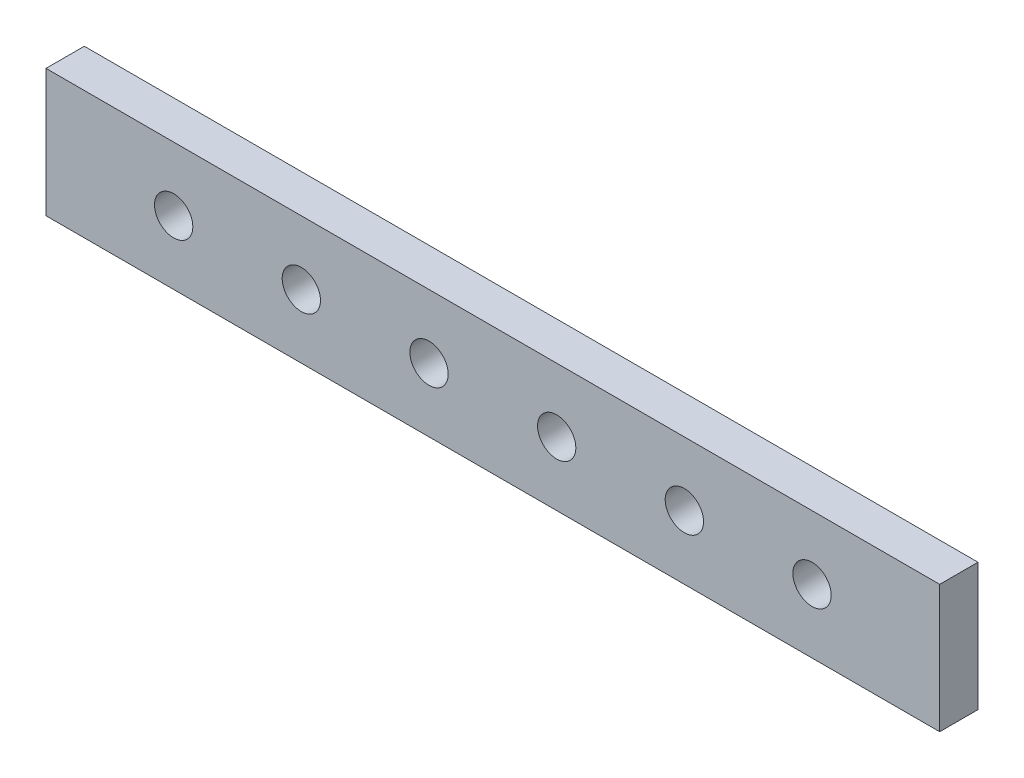
SolidWorks part; units mm, degrees
material "Maple"
ref_plane "Front Plane" through (0, 0, 0) normal (0, 0, 1) x (1, 0, 0)
ref_plane "Top Plane" through (0, 0, 0) normal (0, 1, 0) x (1, 0, 0)
ref_plane "Right Plane" through (0, 0, 0) normal (1, 0, 0) x (0, 0, -1)
sketch "Sketch1" plane through (0, 0, 0) normal (0, 0, 1) x (1, 0, 0)
  line L0 (-25, 0) -> (-35, 0) construction
  line L1 (-35, 5) -> (35, 5)
  line L2 (-35, 5) -> (-35, -5)
  line L3 (-35, -5) -> (35, -5)
  line L4 (35, 5) -> (35, -5)
  line L5 (-35, 5) -> (35, -5) construction
  line L6 (-35, -5) -> (35, 5) construction
  line L7 (-25, 0) -> (-15, 0) construction
  line L8 (-15, 0) -> (-5, 0) construction
  line L9 (-5, 0) -> (5, 0) construction
  line L10 (5, 0) -> (15, 0) construction
  line L11 (15, 0) -> (25, 0) construction
  line L14 (-25, 0) -> (-25, 5) construction
  line L15 (-25, 0) -> (-25, -5) construction
  circle A0 centre (-25, 0) radius 1.5
  circle A2 centre (-15, 0) radius 1.5
  circle A3 centre (-5, 0) radius 1.5
  circle A4 centre (5, 0) radius 1.5
  circle A5 centre (15, 0) radius 1.5
  circle A6 centre (25, 0) radius 1.5
  point P0 (0, 0)
  dimension "D5" = 3
  dimension "D1" = 70
  dimension "D2" = 10
  dimension "D3" = 10
extrude "Boss-Extrude1" add sketch "Sketch1" along normal blind 3
